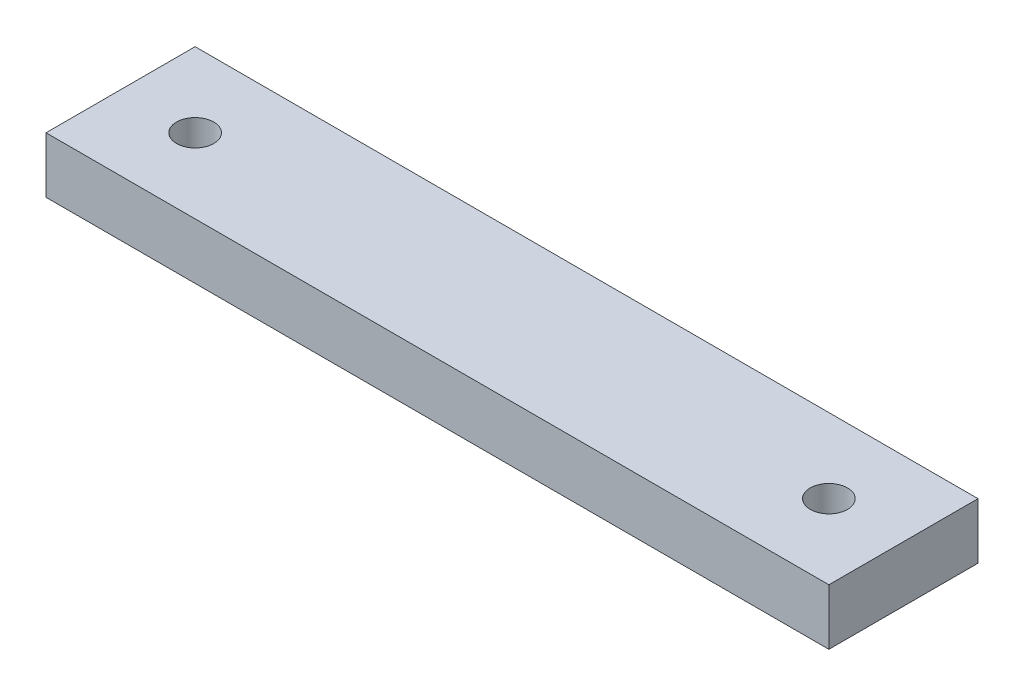
SolidWorks part; units mm, degrees
ref_plane "Front Plane" through (0, 0, 0) normal (0, 0, 1) x (1, 0, 0)
ref_plane "Top Plane" through (0, 0, 0) normal (0, 1, 0) x (1, 0, 0)
ref_plane "Right Plane" through (0, 0, 0) normal (1, 0, 0) x (0, 0, -1)
sketch "Sketch1" plane through (0, 0, 0) normal (0, 1, 0) x (1, 0, 0)
  line L0 (0, -55) -> (0, 55) construction
  line L1 (-105, -20) -> (105, -20)
  line L2 (-105, -20) -> (-105, 20)
  line L3 (-105, 20) -> (105, 20)
  line L4 (105, -20) -> (105, 20)
  line L5 (-105, -20) -> (105, 20) construction
  line L6 (-105, 20) -> (105, -20) construction
  circle A0 centre (-85, 0) radius 5
  circle A1 centre (85, 0) radius 5
  point P1 (0, 0)
  point P8 (0, 0)
  dimension "D3" = 10
  dimension "D1" = 40
  dimension "D2" = 210
  dimension "D4" = 20
extrude "Boss-Extrude1" add sketch "Sketch1" along normal blind 15
